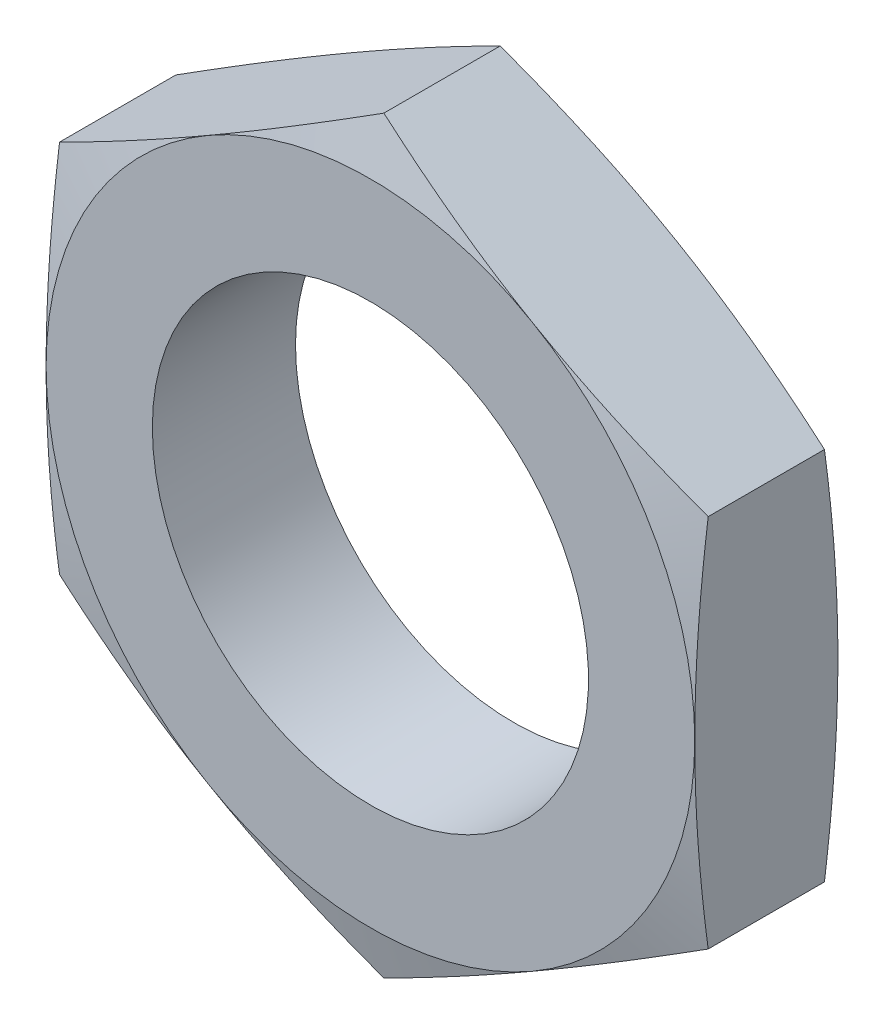
SolidWorks part; units mm, degrees
ref_plane "Plano frontal" through (0, 0, 0) normal (0, 0, 1) x (1, 0, 0)
ref_plane "Plano superior" through (0, 0, 0) normal (0, 1, 0) x (1, 0, 0)
ref_plane "Plano direito" through (0, 0, 0) normal (1, 0, 0) x (0, 0, -1)
sketch "Esboço1" plane through (0, 0, 0) normal (0, 0, 1) x (1, 0, 0)
  line L1 (0, 16.7432) -> (-14.5, 8.3716)
  line L2 (-14.5, 8.3716) -> (-14.5, -8.3716)
  line L3 (-14.5, -8.3716) -> (0, -16.7432)
  line L4 (0, -16.7432) -> (14.5, -8.3716)
  line L5 (14.5, -8.3716) -> (14.5, 8.3716)
  line L6 (14.5, 8.3716) -> (0, 16.7432)
  circle A0 centre (0, 0) radius 14.5 construction
  dimension "D1" = 29
extrude "Ressalto-extrusão1" add sketch "Esboço1" along normal blind 6.4
sketch "Esboço2" plane through (0, 0, 6.4) normal (0, 0, 1) x (1, 0, 0)
  circle A0 centre (0, 0) radius 14.5
extrude "Corte-extrusão1" cut sketch "Esboço2" against normal blind 15 draft 75 flip side to cut
sketch "Esboço3" plane through (0, 0, 0) normal (0, 0, -1) x (-1, 0, 0)
  circle A0 centre (0, 0) radius 14.5
extrude "Corte-extrusão2" cut sketch "Esboço3" against normal blind 15 draft 75 flip side to cut
hole_wizard "Broca de rosquear para tarraxa de M221" positions "Esboço4" profile "Esboço5" hole size "M22" standard "DIN" end condition through all
sketch "Esboço4" plane through (0, 0, 0) normal (0, 0, -1) x (-1, 0, 0)
  point P0 (0, 0)
sketch "Esboço5" plane through (0, 0, 0) normal (1, 0, 0) x (0, 1, 0)
  line L0 (0, 0) -> (0, 6.4)
  line L1 (0, 6.4) -> (9.75, 6.4)
  line L2 (9.75, 6.4) -> (9.75, 0)
  line L5 (9.75, 0) -> (0, 0)
  line L11 (0, -6.35) -> (0, 107.95) construction
  dimension "Thru Hole Dia." = 19.5
  dimension "Thru Hole Depth" = 6.4
cosmetic thread "Representação de rosca1" parameters "D2"=22
